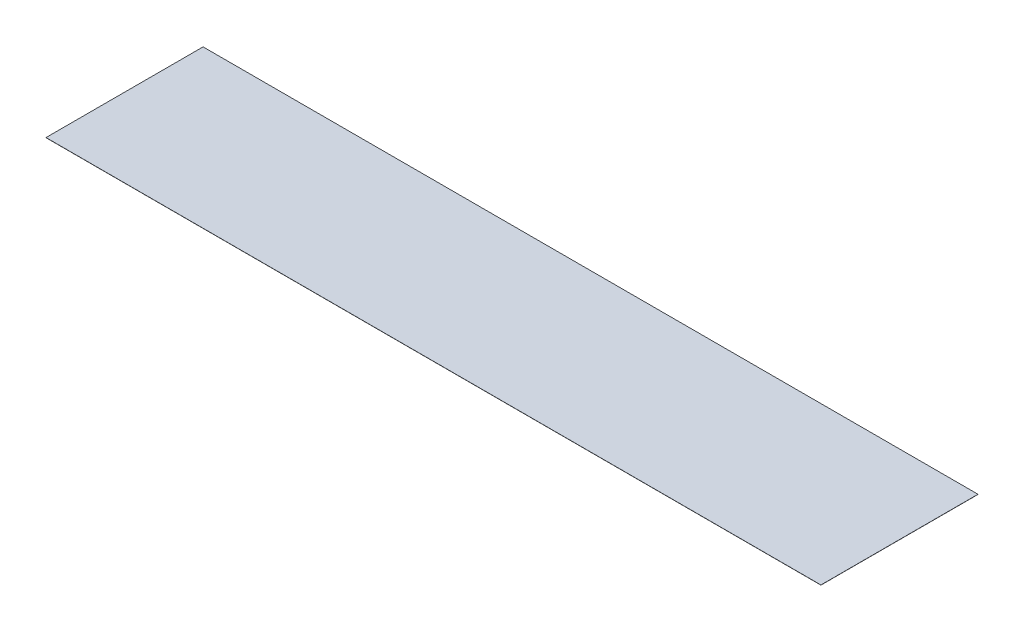
SolidWorks part; units mm, degrees
ref_plane "Front Plane" through (0, 0, 0) normal (0, 0, 1) x (1, 0, 0)
ref_plane "Top Plane" through (0, 0, 0) normal (0, 1, 0) x (1, 0, 0)
ref_plane "Right Plane" through (0, 0, 0) normal (1, 0, 0) x (0, 0, -1)
sketch "Sketch1" plane through (0, 0, 0) normal (0, 1, 0) x (1, 0, 0)
  line L1 (-11277.6, 0) -> (11277.6, 0)
  line L2 (-11277.6, 0) -> (-11277.6, 4572)
  line L3 (-11277.6, 4572) -> (11277.6, 4572)
  line L4 (11277.6, 0) -> (11277.6, 4572)
  point P4 (0, 0)
  point P5 (0, 0)
  dimension "D1" = 4572
  dimension "D2" = 22555.2
extrude "Boss-Extrude1" add sketch "Sketch1" along normal blind 4.7752
ref_plane "Plane1" through (0, 0, 0) normal (1, 0, 0) x (0, 0, -1)
